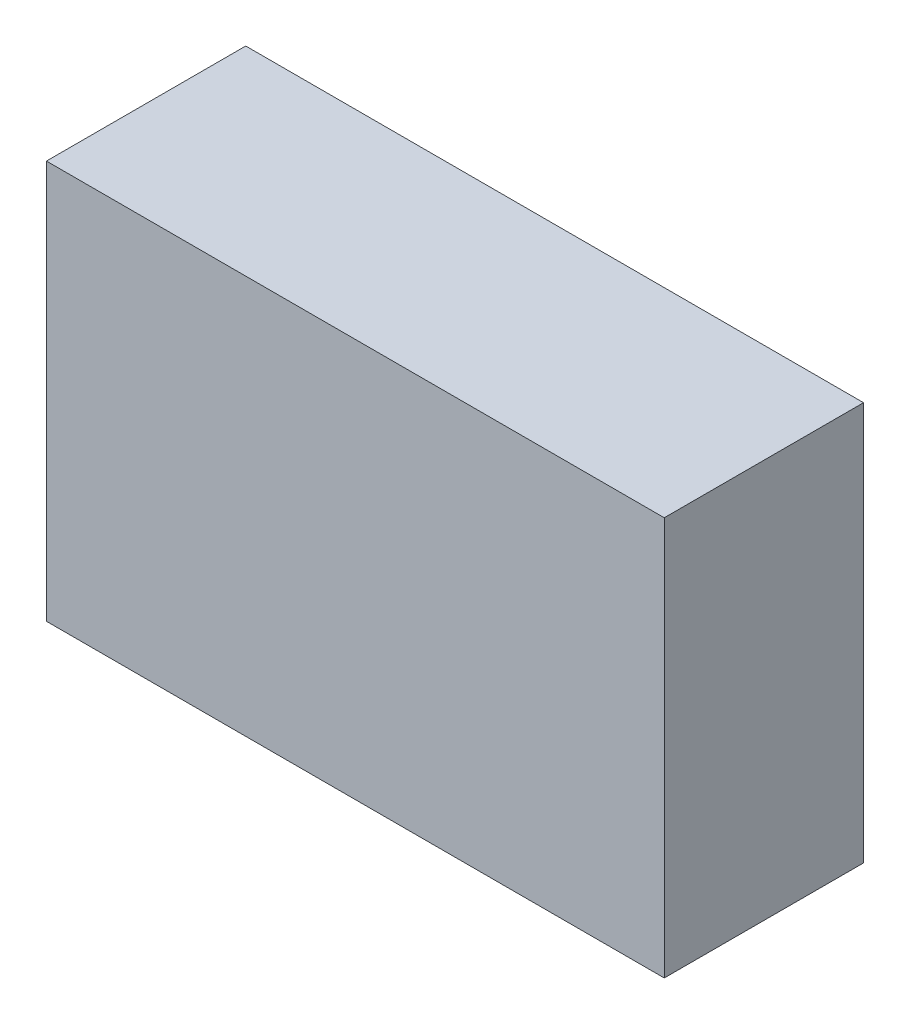
SolidWorks part; units mm, degrees
ref_plane "Front Plane" through (0, 0, 0) normal (0, 0, 1) x (1, 0, 0)
ref_plane "Top Plane" through (0, 0, 0) normal (0, 1, 0) x (1, 0, 0)
ref_plane "Right Plane" through (0, 0, 0) normal (1, 0, 0) x (0, 0, -1)
sketch "Sketch1" plane through (0, 0, 0) normal (0, 0, 1) x (1, 0, 0)
  line L1 (0, 0) -> (31, 0)
  line L2 (0, 0) -> (0, 20)
  line L3 (0, 20) -> (31, 20)
  line L4 (31, 0) -> (31, 20)
extrude "Boss-Extrude1" add sketch "Sketch1" along normal blind 10
